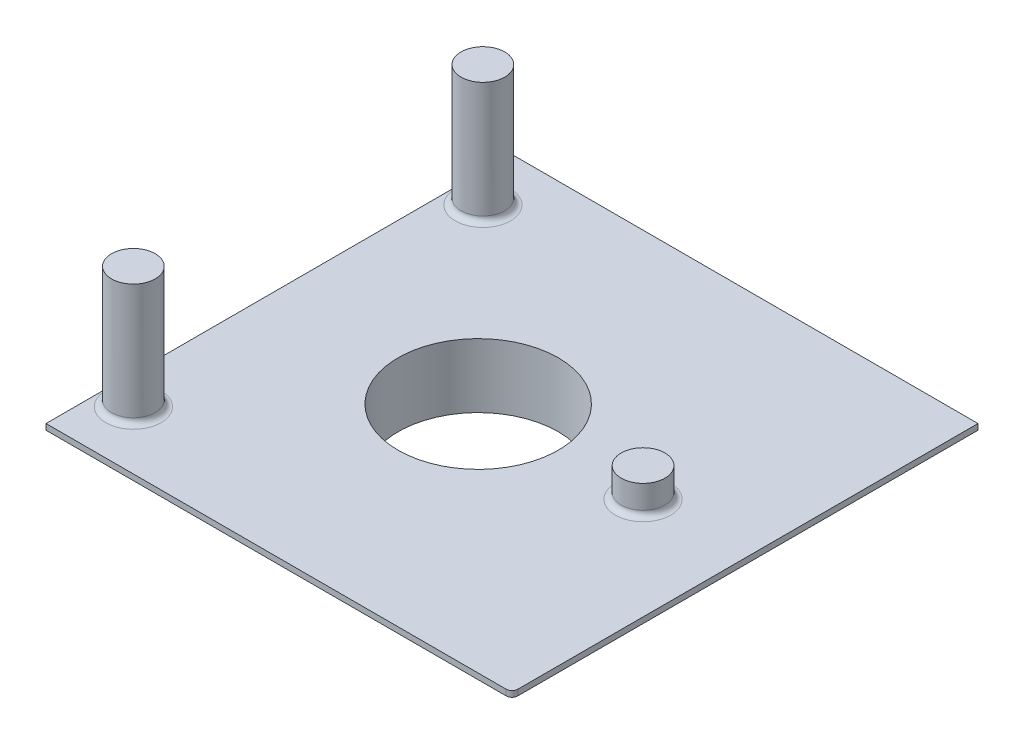
SolidWorks part; units mm, degrees
ref_plane "Front Plane" through (0, 0, 0) normal (0, 0, 1) x (1, 0, 0)
ref_plane "Top Plane" through (0, 0, 0) normal (0, 1, 0) x (1, 0, 0)
ref_plane "Right Plane" through (0, 0, 0) normal (1, 0, 0) x (0, 0, -1)
sketch "Sketch1" plane through (0, 0, 0) normal (0, 1, 0) x (1, 0, 0)
  line L1 (-101.6, 101.6) -> (101.6, 101.6)
  line L2 (-101.6, 101.6) -> (-101.6, -101.6)
  line L3 (-101.6, -101.6) -> (101.6, -101.6)
  line L4 (101.6, 101.6) -> (101.6, -101.6)
  line L5 (-101.6, 101.6) -> (101.6, -101.6) construction
  line L6 (-101.6, -101.6) -> (101.6, 101.6) construction
  point P0 (0, 0)
  dimension "D1" = 203.2
  dimension "D2" = 203.2
  dimension "D3" = 101.6
extrude "Boss-Extrude1" add sketch "Sketch1" along normal blind 2.54
sketch "Sketch3" plane through (0, 2.54, 0) normal (0, 1, 0) x (1, 0, 0)
  circle A0 centre (57.15, 0) radius 9.525
  dimension "D1" = 19.05
  dimension "D2" = 57.15
extrude "Boss-Extrude2" add sketch "Sketch3" along normal blind 12.7
sketch "Sketch4" plane through (0, 2.54, 0) normal (0, 1, 0) x (1, 0, 0)
  line L2 (57.15, 0) -> (-14.742, 0) construction
  circle A2 centre (-14.742, 0) radius 38.1
  dimension "D1" = 76.2
sketch "Sketch5" plane through (0, 2.54, 0) normal (0, 1, 0) x (1, 0, 0)
  circle A0 centre (-14.742, 0) radius 34.925
  dimension "D1" = 69.85
  dimension "D2" = 14.742
extrude "Cut-Extrude2" cut sketch "Sketch5" against normal through all
sketch "Sketch6" plane through (0, 0, 0) normal (0, 1, 0) x (1, 0, 0)
  circle A0 centre (57.15, 0) radius 139.7 construction
  dimension "D1" = 279.4
sketch "Sketch7" plane through (0, 2.54, 0) normal (0, 1, 0) x (1, 0, 0)
  circle A0 centre (57.15, 0) radius 139.7 construction
  circle A1 centre (-88.9, 76.2) radius 9.525
  dimension "D1" = 279.4
  dimension "D2" = 76.2
  dimension "D4" = 19.05
  dimension "D3" = 88.9
extrude "Boss-Extrude4" add sketch "Sketch7" along normal offset from surface (53.0225 mm away) 55.5625 up to face at (-14.742, 0, 34.925)
mirror "Mirror1" about plane through (0, 0, 0) normal (0, 0, 1) of "Boss-Extrude4"
fillet "Fillet1" radius 2.54 1 edges at (101.6, 1.27, 101.6)
sketch "Sketch8" plane through (0, 0, 0) normal (0, -1, 0) x (1, 0, 0)
  circle A0 centre (-14.742, 0) radius 34.925
  circle A1 centre (-14.742, 0) radius 40.005
  dimension "D1" = 69.85
  dimension "D2" = 5.08
extrude "Boss-Extrude5" add sketch "Sketch8" along normal blind 25.4
fillet "Fillet2" radius 2.54 3 edges at (57.15, 2.54, 9.525) (-88.9, 2.54, -66.675) (-88.9, 2.54, 85.725)
